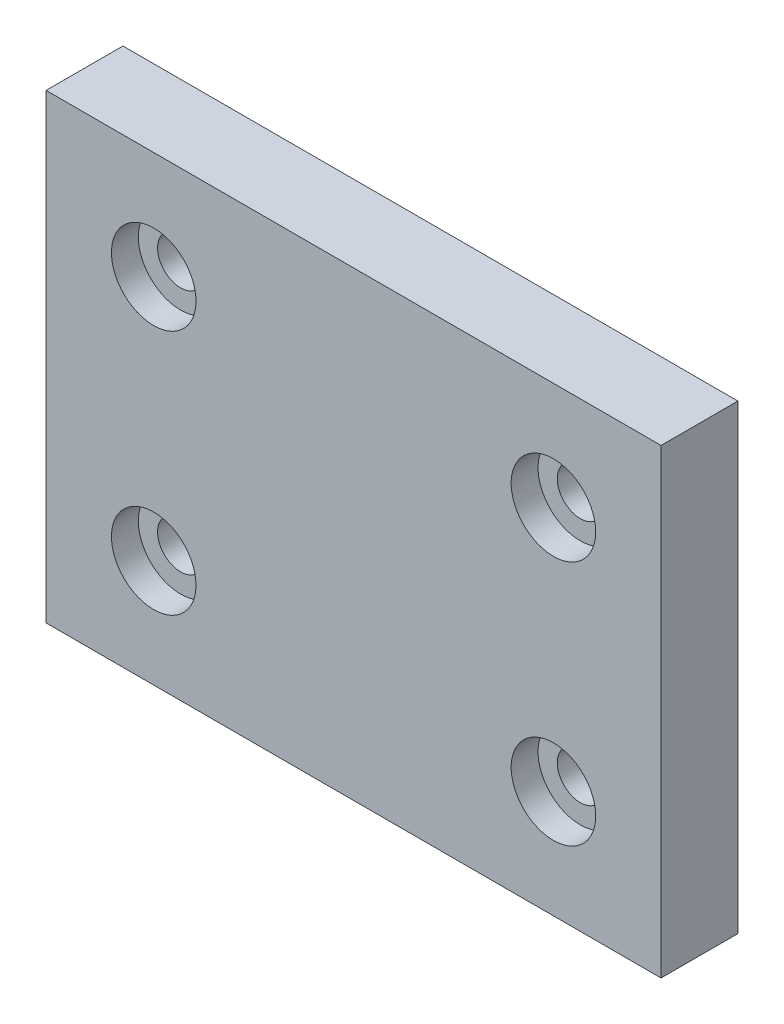
SolidWorks part; units mm, degrees
ref_plane "前视基准面" through (0, 0, 0) normal (0, 0, 1) x (1, 0, 0)
ref_plane "上视基准面" through (0, 0, 0) normal (0, 1, 0) x (1, 0, 0)
ref_plane "右视基准面" through (0, 0, 0) normal (1, 0, 0) x (0, 0, -1)
sketch "草图1" plane through (0, 0, 0) normal (0, 0, 1) x (1, 0, 0)
  line L0 (-40, -30) -> (40, -30)
  line L1 (40, -30) -> (40, 30)
  line L2 (40, 30) -> (-40, 30)
  line L3 (-40, 30) -> (-40, -30)
extrude "凸台-拉伸1" add sketch "草图1" along normal blind 10
ref_plane "基准面1" through (0, 0, 10) normal (0, 0, 1) x (1, 0, 0)
sketch "草图2" plane through (0, 0, 10) normal (0, 0, 1) x (1, 0, 0)
  circle A0 centre (26, 16) radius 5.5
  circle A1 centre (26, -16) radius 5.5
  circle A2 centre (-26, 16) radius 5.5
  circle A3 centre (-26, -16) radius 5.5
extrude "切除-拉伸1" cut sketch "草图2" against normal blind 3.5
sketch "草图3" plane through (0, 0, 10) normal (0, 0, 1) x (1, 0, 0)
  circle A0 centre (26, 16) radius 3
  circle A1 centre (26, -16) radius 3
  circle A2 centre (-26, 16) radius 3
  circle A3 centre (-26, -16) radius 3
extrude "切除-拉伸2" cut sketch "草图3" against normal through all
